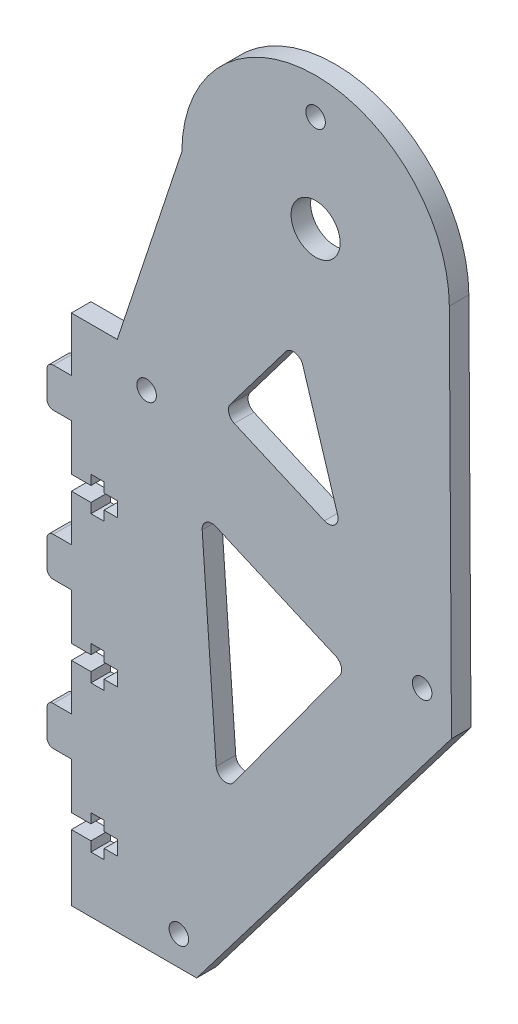
SolidWorks part; units mm, degrees
ref_plane "前视基准面" through (0, 0, 0) normal (0, 0, 1) x (1, 0, 0)
ref_plane "上视基准面" through (0, 0, 0) normal (0, 1, 0) x (1, 0, 0)
ref_plane "右视基准面" through (0, 0, 0) normal (1, 0, 0) x (0, 0, -1)
sketch "草图1" plane through (0, 0, 0) normal (0, 0, 1) x (1, 0, 0)
  line L4 (348.5429, 4.8543) -> (428.5429, 4.8543) construction
  line L11 (348.5429, 4.8543) -> (298.5429, 4.8543) construction
  line L15 (298.5515, -96.6457) -> (302.5515, -96.6457)
  line L16 (302.5515, -96.6457) -> (302.5515, -98.6442)
  line L17 (302.5515, -98.6442) -> (305.2515, -98.6442)
  line L18 (305.2515, -98.6442) -> (305.2515, -96.6457)
  line L19 (305.2515, -96.6457) -> (307.9515, -96.6457)
  line L20 (307.9515, -96.6457) -> (307.9515, -93.6457)
  line L21 (307.9515, -93.6457) -> (305.2515, -93.6457)
  line L22 (305.2515, -93.6457) -> (305.2515, -91.6472)
  line L23 (305.2515, -91.6472) -> (302.5515, -91.6472)
  line L24 (302.5515, -91.6472) -> (302.5515, -93.6457)
  line L25 (302.5515, -93.6457) -> (298.5515, -93.6457)
  line L27 (298.5429, -95.1457) -> (302.5429, -95.1457) construction
  line L28 (298.5515, -110.1457) -> (303.5515, -110.1457) construction
  line L29 (303.5515, -114.1457) -> (293.5515, -114.1457) construction
  line L30 (303.5515, -114.1457) -> (303.5515, -106.1457) construction
  line L31 (303.5515, -106.1457) -> (293.5515, -106.1457) construction
  line L32 (293.5515, -114.1457) -> (293.5515, -106.1457)
  line L33 (303.5515, -114.1457) -> (293.5515, -106.1457) construction
  line L34 (303.5515, -106.1457) -> (293.5515, -114.1457) construction
  line L35 (302.5515, -126.6457) -> (298.5515, -126.6457)
  line L36 (298.5515, -123.6457) -> (302.5515, -123.6457)
  line L37 (302.5515, -128.6442) -> (302.5515, -126.6457)
  line L38 (305.2515, -128.6442) -> (302.5515, -128.6442)
  line L39 (305.2515, -126.6457) -> (305.2515, -128.6442)
  line L40 (307.9515, -126.6457) -> (305.2515, -126.6457)
  line L41 (307.9515, -123.6457) -> (307.9515, -126.6457)
  line L42 (305.2515, -123.6457) -> (307.9515, -123.6457)
  line L43 (305.2515, -121.6473) -> (305.2515, -123.6457)
  line L44 (302.5515, -121.6473) -> (305.2515, -121.6473)
  line L45 (302.5515, -123.6457) -> (302.5515, -121.6473)
  line L46 (293.5515, -76.1457) -> (293.5515, -84.1457)
  line L47 (302.5515, -63.6457) -> (298.5515, -63.6457)
  line L48 (298.5515, -66.6457) -> (302.5515, -66.6457)
  line L49 (302.5515, -66.6457) -> (302.5515, -68.6442)
  line L50 (302.5515, -68.6442) -> (305.2515, -68.6442)
  line L51 (305.2515, -68.6442) -> (305.2515, -66.6457)
  line L52 (305.2515, -66.6457) -> (307.9515, -66.6457)
  line L53 (307.9515, -66.6457) -> (307.9515, -63.6457)
  line L54 (307.9515, -63.6457) -> (305.2515, -63.6457)
  line L55 (305.2515, -63.6457) -> (305.2515, -61.6472)
  line L56 (305.2515, -61.6472) -> (302.5515, -61.6472)
  line L57 (302.5515, -61.6472) -> (302.5515, -63.6457)
  line L58 (293.5515, -84.1457) -> (298.5515, -84.1457)
  line L59 (293.5515, -76.1457) -> (298.5515, -76.1457)
  line L60 (298.5515, -76.1457) -> (298.5515, -66.6457)
  line L61 (298.5515, -84.1457) -> (298.5515, -93.6457)
  line L62 (298.5515, -96.6457) -> (298.5515, -106.1457)
  line L63 (298.5515, -106.1457) -> (293.5515, -106.1457)
  line L64 (293.5515, -114.1457) -> (298.5515, -114.1457)
  line L65 (298.5515, -114.1457) -> (298.5515, -123.6457)
  line L66 (307.9515, -65.1457) -> (305.2429, -65.1457) construction
  line L67 (293.5515, -46.1457) -> (298.5515, -46.1457)
  line L68 (293.5515, -54.1457) -> (293.5515, -46.1457)
  line L69 (293.5515, -54.1457) -> (298.5515, -54.1457)
  line L70 (298.5515, -54.1457) -> (298.5515, -63.6457)
  line L78 (298.5515, -126.6457) -> (298.5515, -140.1457)
  line L79 (298.5515, -140.1457) -> (324.1947, -140.1457)
  line L81 (375.9264, 4.8543) -> (376.3645, -71.6457)
  line L84 (376.3645, -71.6457) -> (324.1947, -140.1457)
  line L85 (298.5515, -46.1457) -> (298.5515, -35.0457)
  line L87 (298.5515, -35.0457) -> (307.9429, -35.0457)
  line L88 (307.9429, -35.0457) -> (321.1593, 4.8543)
  line L89 (320.5515, -134.1457) -> (313.9429, -41.0457) construction
  line L90 (313.9429, -41.0457) -> (370.3645, -65.6457) construction
  line L91 (370.3645, -65.6457) -> (320.5515, -134.1457) construction
  line L92 (354.9532, -69.8355) -> (328.5855, -106.0948)
  line L93 (328.5855, -106.0948) -> (325.0873, -56.8139)
  line L94 (325.0873, -56.8139) -> (354.9532, -69.8355)
  line L95 (370.3645, -65.6457) -> (348.5429, 4.6975) construction
  line L96 (348.5429, 4.6975) -> (313.9429, -41.0457) construction
  line L97 (329.577, -36.9531) -> (354.3432, -47.7512)
  line L98 (354.3432, -47.7512) -> (344.7646, -16.8742)
  line L99 (344.7646, -16.8742) -> (329.577, -36.9531)
  circle A11 centre (348.5429, 4.8543) radius 5.0225
  circle A14 centre (348.5429, 4.8543) radius 27.3835 construction
  arc A22 (375.9264, 4.8543) -> (321.1593, 4.8543) centre (348.5429, 4.6975) ccw
  circle A23 centre (348.5429, 24.6975) radius 2
  circle A24 centre (320.5515, -134.1457) radius 2
  circle A25 centre (370.3645, -65.6457) radius 2
  circle A26 centre (313.9429, -41.0457) radius 2
  point P30 (298.5515, -110.1457)
  dimension "D2" = 20
  dimension "D3" = 3
  dimension "D4" = 10.045
  dimension "D5" = 2.7
  dimension "D6" = 50
  dimension "D15" = 22
  dimension "D17" = 6
  dimension "D19" = 6
  dimension "D7" = 80
  dimension "D8" = 4
  dimension "D9" = 1.5
  dimension "D10" = 15
  dimension "D11" = 8
  dimension "D12" = 10
  dimension "D13" = 100
  dimension "D14" = 13.5
  dimension "D16" = 6
  dimension "D18" = 6
  dimension "D20" = 6
  dimension "D21" = 10
  dimension "D22" = 10
extrude "凸台-拉伸1" add sketch "草图1" along normal blind 4
sketch "草图2" plane through (298.5515, 0, 0) normal (-1, 0, 0) x (0, 0, 1)
  line L0 (2, -66.6457) -> (2, -63.6457)
  line L1 (4, -66.6457) -> (0, -66.6457) construction
  line L2 (4, -63.6457) -> (0, -63.6457) construction
  circle A0 centre (2, -65.1457) radius 1.5
fillet "圆角1" radius 2 6 edges at (344.7646, -16.8742, 2) (329.577, -36.9531, 2) (354.3432, -47.7512, 2) (325.0873, -56.8139, 2) (328.5855, -106.0948, 2) (354.9532, -69.8355, 2)
fillet "圆角2" radius 1.3 6 edges at (293.5515, -46.1457, 2) (293.5515, -54.1457, 2) (293.5515, -84.1457, 2) (293.5515, -76.1457, 2) (293.5515, -114.1457, 2) (293.5515, -106.1457, 2)
